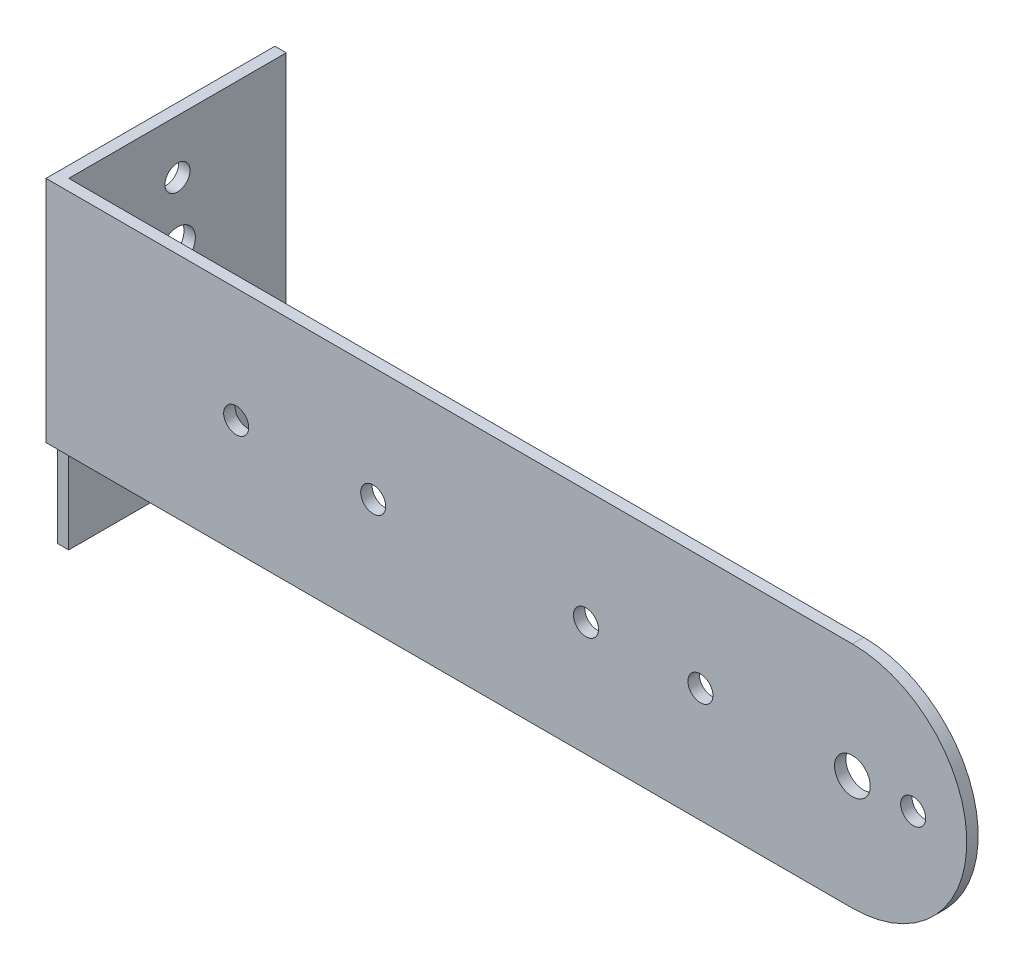
SolidWorks part; units mm, degrees
material "6061 Alloy"
ref_plane "Front Plane" through (0, 0, 0) normal (0, 0, 1) x (1, 0, 0)
ref_plane "Top Plane" through (0, 0, 0) normal (0, 1, 0) x (1, 0, 0)
ref_plane "Right Plane" through (0, 0, 0) normal (1, 0, 0) x (0, 0, -1)
sketch "Sketch1" plane through (0, 0, 0) normal (0, 0, 1) x (1, 0, 0)
  line L0 (0, 16) -> (-112.75, 16)
  line L1 (-112.75, 16) -> (-112.75, -16)
  line L2 (-112.75, -16) -> (0, -16)
  arc A0 (0, -16) -> (0, 16) centre (0, 0) ccw
  dimension "D1" = 32
  dimension "D2" = 112.75
extrude "Boss-Extrude1" add sketch "Sketch1" along normal blind 1.59
sketch "Sketch2" plane through (0, 0, 0) normal (0, 0, -1) x (-1, 0, 0)
  line L1 (112.75, 16) -> (111.16, 16)
  line L2 (112.75, 16) -> (112.75, -29)
  line L3 (112.75, -29) -> (111.16, -29)
  line L4 (111.16, 16) -> (111.16, -29)
  point P5 (111.955, -29)
  point P6 (112.75, -6.5)
  dimension "D1" = 45
  dimension "D2" = 1.59
extrude "Boss-Extrude2" add sketch "Sketch2" along normal blind 30.41
sketch "Sketch3" plane through (0, 0, 0) normal (0, 0, -1) x (-1, 0, 0)
  line L0 (-40.1644, 0) -> (163.0587, 0) construction
  line L1 (111.16, 16) -> (111.16, -16) construction
  circle A0 centre (86.16, 0) radius 1.75
  circle A1 centre (37.25, 0) radius 1.75
  circle A2 centre (67, 0) radius 1.75
  circle A3 centre (-8.5, 0) radius 1.75
  circle A4 centre (0, 0) radius 2.5
  circle A5 centre (21.25, 0) radius 1.75
  dimension "D6" = 5
  dimension "D7" = 29.75
  dimension "D3" = 3.5
  dimension "D1" = 8.5
  dimension "D2" = 29.75
  dimension "D4" = 16
  dimension "D5" = 25
extrude "Cut-Extrude1" cut sketch "Sketch3" against normal through all
sketch "Sketch4" plane through (-112.75, 0, 0) normal (-1, 0, 0) x (0, 0, 1)
  line L0 (-15.205, 26.9729) -> (-15.205, -41.0088) construction
  line L1 (-30.41, -29) -> (-30.41, 16) construction
  circle A0 centre (-15.205, 0) radius 2.5
  circle A1 centre (-15.205, 8.5) radius 1.75
  circle A2 centre (-15.205, -21.25) radius 1.75
  dimension "D4" = 3.5
  dimension "D5" = 5
  dimension "D1" = 15.205
  dimension "D2" = 8.5
  dimension "D3" = 29.75
extrude "Cut-Extrude2" cut sketch "Sketch4" against normal blind 30.41
